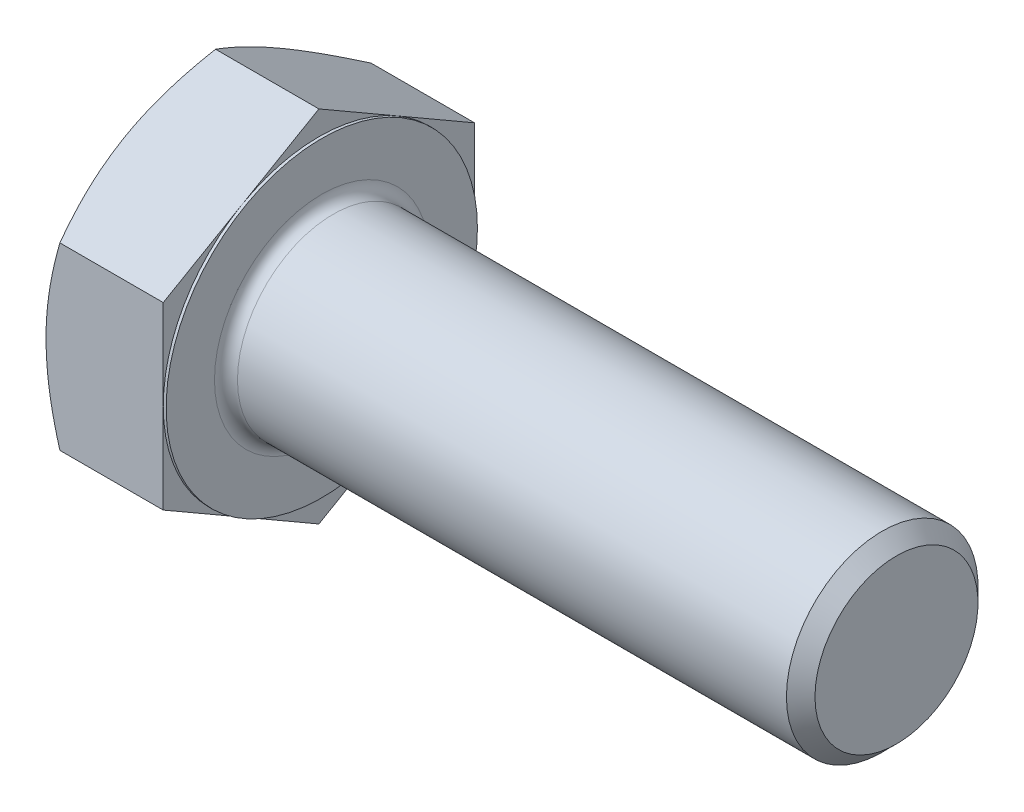
SolidWorks part; units mm, degrees
extrude "BaseHead" add sketch "Sketch1" along normal blind 15.9258
sketch "Sketch1" plane through (0, 0, 0) normal (1, 0, 0) x (0, 0, -1)
  line L0 (20.6375, 11.9151) -> (20.6375, -11.9151)
  line L1 (-20.6375, 11.9151) -> (-20.6375, -11.9151)
  line L2 (20.6375, -11.9151) -> (0, -23.8301)
  line L3 (0, -23.8301) -> (-20.6375, -11.9151)
  line L4 (20.6375, 11.9151) -> (0, 23.8301)
  line L5 (0, 23.8301) -> (-20.6375, 11.9151)
  dimension "Width_flats" = 41.275
  dimension "D2" = 120
  dimension "D3" = 20.6375
  dimension "D4" = 20.6375
  dimension "D5" = 20.6375
revolve "HeadChamfer" cut sketch "Sketch3" angle 360 about L6
sketch "Sketch3" plane through (0, 0, 0) normal (0, 0, 1) x (1, 0, 0)
  line L0 (0, 20.6375) -> (5.5094, 30.1801)
  line L1 (0, 23.8301) -> (0, 11.9151) construction
  line L2 (5.5094, 30.1801) -> (5.5094, 36.5301)
  line L3 (5.5094, 36.5301) -> (-12.7, 36.5301)
  line L4 (-12.7, 36.5301) -> (-12.7, 20.6375)
  line L5 (-12.7, 20.6375) -> (0, 20.6375)
  line L6 (0, 0) -> (99.06, 0) construction
  line L7 (15.9258, 23.8301) -> (0, 23.8301) construction
  dimension "D1" = 20.6375
  dimension "D2" = 6.35
  dimension "D3" = 12.7
  dimension "D4" = 6.35
  dimension "Head_ch_ang" = 30
ref_plane "Plane1" through (0, 0, 0) normal (0, 0, 1) x (1, 0, 0)
ref_plane "Plane2" through (0, 0, 0) normal (0, 1, 0) x (1, 0, 0)
ref_plane "Plane3" through (0, 0, 0) normal (1, 0, 0) x (0, 0, -1)
sketch "BodySke" plane through (0, 0, 0) normal (0, 0, 1) x (1, 0, 0)
  line L0 (0, 11.9151) -> (0, -11.9151) construction
  line L1 (0, 0) -> (92.1258, 0)
  line L2 (0, 0) -> (0, 12.7)
  line L3 (0, 12.7) -> (90.2335, 12.7)
  line L4 (92.1258, 0) -> (92.1258, 10.8077)
  line L5 (15.9258, 23.8301) -> (15.9258, 11.9151) construction
  line L6 (92.1258, 10.8077) -> (90.2335, 12.7)
  line L7 (0, 0) -> (96.52, 0) construction
  line L8 (92.1258, -10.8077) -> (90.2335, -12.7) construction
  line L9 (0, -12.7) -> (90.2335, -12.7) construction
  line L10 (18.034, 15.24) -> (18.034, -1.27) construction
  line L11 (60.3758, 15.24) -> (60.3758, -1.27) construction
  line L12 (15.9258, 11.9151) -> (15.9258, -11.9151) construction
  dimension "Diameter" = 25.4
revolve "BaseBody" add sketch "BodySke" angle 360 about L7
cosmetic thread "ThreadCosmetic" [suppressed] parameters "Thread_length"=31.75, "Thread_minor"=21.6154
sketch "Sketch4" plane through (0, 0, 0) normal (0, 0, 1) x (1, 0, 0)
  line L1 (15.9258, 23.8301) -> (15.9258, 11.9151) construction
  line L2 (15.9258, 20.6375) -> (15.5448, 20.6375)
  line L3 (15.9258, 20.6375) -> (15.9258, 49.2301)
  line L4 (15.9258, 49.2301) -> (15.5448, 49.2301)
  line L5 (0, 0) -> (95.25, 0) construction
  line L6 (0, 0) -> (96.52, 0) construction
  line L7 (15.5448, 20.6375) -> (15.5448, 49.2301)
  line L8 (15.9258, 23.8301) -> (1.8433, 23.8301) construction
  dimension "D1" = 20.6375
  dimension "D2" = 25.4
revolve "BearingFace" cut sketch "Sketch4" angle 360 about L5
fillet "HeadFillet" radius 1.524 1 edges at (15.9258, 0, -12.7)
sketch "ThdSchSke" plane through (0, 0, 0) normal (0, 0, 1) x (1, 0, 0)
  line L0 (60.3758, -10.8077) -> (59.0508, -12.7)
  line L1 (60.3758, -10.8077) -> (61.7008, -12.7)
  line L2 (61.7008, -12.7) -> (61.7008, -15.875)
  line L3 (-3.175, 0) -> (5.1513, 0) construction
  line L5 (61.7008, -15.875) -> (59.0508, -15.875)
  line L6 (59.0508, -15.875) -> (59.0508, -12.7)
  dimension "Thread_minor" = 21.6154
  dimension "Diameter" = 25.4
  dimension "Start" = 60.3758
revolve "ThreadSchematic" [suppressed] cut sketch "ThdSchSke" angle 360 about L3
pattern_linear "ThdSchPat" [suppressed]
equation "\"D3@Sketch1\" = \"Width_flats@Sketch1\" / 2"
equation "\"D4@Sketch1\" = \"D3@Sketch1\""
equation "\"D5@Sketch1\" = \"D4@Sketch1\""
equation "\"Thread_minor@ThreadCosmetic\" = \"Minor_dia@BodySke\""
equation "\"D1@Sketch3\" = \"Width_flats@Sketch1\" / 2"
equation "\"D1@Sketch4\" = \"Width_flats@Sketch1\" / 2"
equation "\"Thread_length@ThreadCosmetic\" = ((sgn( (\"Length@BodySke\" - \"Advance@BodySke\" ) - \"Thread_nom@BodySke\" )-1)*( (\"Length@BodySke\" - \"Advance@BodySke\" ) - \"Thread_nom@BodySke\" ))/-2+ \"Thread_nom@BodySke\""
equation "\"Thread_minor@ThdSchSke\" = \"Minor_dia@BodySke\""
equation "\"Diameter@ThdSchSke\" = \"Diameter@BodySke\""
equation "\"Overcut@ThdSchSke\" = \"Diameter@BodySke\" * 1.25"
equation "\"Start@ThdSchSke\" = \"Head_ht@BaseHead\" + \"Length@BodySke\" - \"Thread_length@ThreadCosmetic\"  '---Non-countersunk---"
equation "\"Num_threads@ThdSchPat\" = int( \"Thread_length@ThreadCosmetic\" / \"Advance@BodySke\" + 0.999 )  + 1"
equation "\"Advance@ThdSchPat\" = \"Thread_length@ThreadCosmetic\" /  (\"Num_threads@ThdSchPat\" - 1) 'relax it"
equation "\"Num_threads@ThdSchPat\" = \"Num_threads@ThdSchPat\" - sgn( \"Num_threads@ThdSchPat\" - 1) '---chamfered tips only---"
